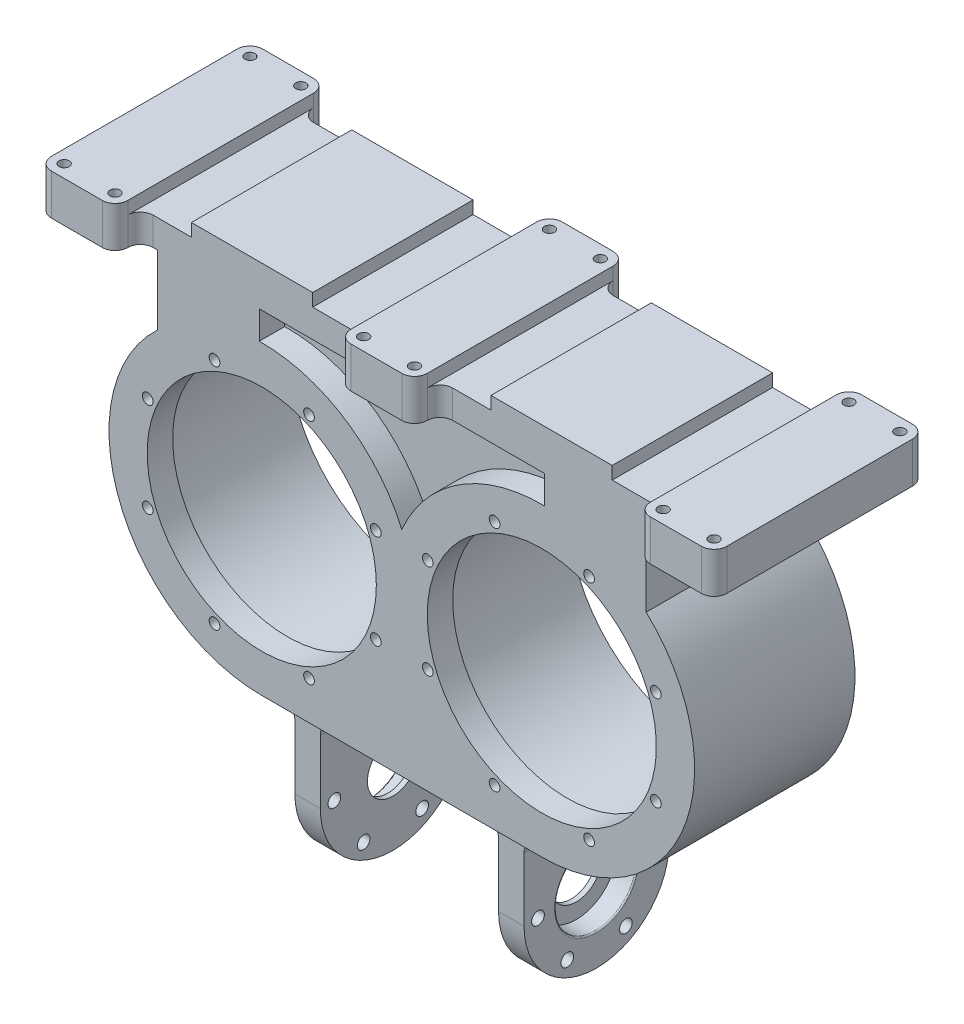
SolidWorks part; units mm, degrees
material "不锈钢 (铁素体)"
ref_plane "前视基准面" through (0, 0, 0) normal (0, 0, 1) x (1, 0, 0)
ref_plane "上视基准面" through (0, 0, 0) normal (0, 1, 0) x (1, 0, 0)
ref_plane "右视基准面" through (0, 0, 0) normal (1, 0, 0) x (0, 0, -1)
other "Configuration Table"
sketch "草图1" plane through (0, 0, 0) normal (0, 0, 1) x (1, 0, 0)
  line L0 (55, 3.4264) -> (55, 82.0697) construction
  line L1 (0, 0) -> (0, 52.5) construction
  line L2 (-40.9852, 43.8203) -> (-40.9852, 71.042)
  line L4 (110, 0) -> (110, 52.5) construction
  line L8 (150.9852, 43.8203) -> (150.9852, 71.042)
  line L10 (150.9852, 82.0697) -> (-40.9852, 82.0697)
  line L14 (0, -60) -> (110, -60)
  line L15 (-40.9852, 71.042) -> (-77.642, 71.042)
  line L16 (-77.642, 71.042) -> (-77.642, 82.0697)
  line L17 (-77.642, 82.0697) -> (-40.9852, 82.0697)
  line L18 (187.642, 82.0697) -> (150.9852, 82.0697)
  line L19 (150.9852, 71.042) -> (187.642, 71.042)
  line L20 (187.642, 71.042) -> (187.642, 82.0697)
  circle A0 centre (0, 0) radius 52.5
  arc A1 (-40.9852, 43.8203) -> (0, -60) centre (0, 0) ccw
  arc A2 (150.9852, 43.8203) -> (110, -60) centre (110, 0) cw
  circle A3 centre (110, 0) radius 52.5
  dimension "D1" = 105
  dimension "D2" = 60
  dimension "D3" = 110
extrude "凸台-拉伸1" add sketch "草图1" along normal blind 63
ref_plane "中心堆成面" through (55, 0, 0) normal (1, 0, 0) x (0, 0, -1)
ref_plane "基准面2" through (10, 0, 0) normal (1, 0, 0) x (0, 0, -1)
sketch "草图3" plane through (10, 0, 0) normal (1, 0, 0) x (0, 0, -1)
  line L6 (-60, -60) -> (-60, -90)
  line L7 (-63, -60) -> (0, -60) construction
  line L9 (-3, -90) -> (-3, -60)
  line L10 (-3, -60) -> (-60, -60)
  line L11 (-63, 43.8203) -> (-63, -60) construction
  line L12 (0, -60) -> (0, 43.8203) construction
  arc A4 (-60, -90) -> (-3, -90) centre (-31.5, -90) ccw
  circle A5 centre (-31.5, -90) radius 10
  dimension "D3" = 20
  dimension "D1" = 3
  dimension "D2" = 3
  dimension "D4" = 30
extrude "凸台-拉伸3" add sketch "草图3" along normal blind 10
sketch "草图5" plane through (0, 0, 3) normal (0, 0, -1) x (-1, 0, 0)
  line L1 (-15, -90) -> (-15, -82.99) construction
  line L5 (-20, -90) -> (-10, -90) construction
  line L6 (-20, -90) -> (-20, -60) construction
  line L7 (0, -60) -> (-110, -60) construction
  line L8 (-20, -65) -> (-20, -60)
  line L9 (-20, -60) -> (-25, -60)
  line L10 (-10, -65) -> (-10, -60)
  line L11 (-10, -60) -> (-5, -60)
  arc A1 (-20, -65) -> (-25, -60) centre (-25, -65) ccw
  arc A2 (-10, -65) -> (-5, -60) centre (-5, -65) cw
  dimension "D1" = 5
  dimension "D2" = 5
extrude "凸台-拉伸5" add sketch "草图5" against normal up to surface (57 mm away) up to face at (15, -75, 60)
mirror "镜向1" about plane through (55, 0, 0) normal (1, 0, 0) of "凸台-拉伸5", "凸台-拉伸3"
sketch "草图6" plane through (0, 0, 63) normal (0, 0, 1) x (1, 0, 0)
  line L0 (55, -34.65) -> (55, 34.65) construction
  circle A1 centre (0, 0) radius 45
  circle A3 centre (110, 0) radius 45
  circle A6 centre (0, 0) radius 52.5
  circle A7 centre (110, 0) radius 52.5
extrude "凸台-拉伸6" add sketch "草图6" against normal blind 10
sketch "草图9" plane through (0, 0, 63) normal (0, 0, 1) x (1, 0, 0)
  line L0 (61.5, 0) -> (110, 0) construction
  line L1 (110, 0) -> (89.2277, 8.6042) construction
  circle A0 centre (110, 0) radius 48.5 construction
  circle A1 centre (65.1918, 18.5601) radius 2.1
  circle A2 centre (91.4399, 44.8082) radius 2.1
  circle A3 centre (128.5601, 44.8082) radius 2.1
  circle A4 centre (154.8082, 18.5601) radius 2.1
  circle A5 centre (154.8082, -18.5601) radius 2.1
  circle A6 centre (128.5601, -44.8082) radius 2.1
  circle A7 centre (91.4399, -44.8082) radius 2.1
  circle A8 centre (65.1918, -18.5601) radius 2.1
  dimension "D1" = 8
  dimension "D2" = 22.5
  dimension "D3" = 48.5
extrude "切除-拉伸1" cut sketch "草图9" against normal blind 10
mirror "镜向2" about plane through (55, 0, 0) normal (1, 0, 0) of "切除-拉伸1"
sketch "草图10" plane through (0, 0, 63) normal (0, 0, 1) x (1, 0, 0)
  line L1 (110.9852, 59.9919) -> (110.9852, 71.042)
  line L2 (110.9852, 71.042) -> (-0.9852, 71.042)
  line L3 (-0.9852, 71.042) -> (-0.9852, 59.9919)
  line L4 (150.9852, 43.8203) -> (150.9852, 71.042) construction
  line L5 (-40.9852, 71.042) -> (-40.9852, 43.8203) construction
  line L7 (-77.642, 71.042) -> (-40.9852, 71.042) construction
  arc A2 (110.9852, 59.9919) -> (55, 23.9792) centre (110, 0) ccw
  arc A3 (55, 23.9792) -> (-0.9852, 59.9919) centre (0, 0) ccw
  dimension "D1" = 40
  dimension "D3" = 120
  dimension "D4" = 120
  dimension "D2" = 40
  dimension "D5" = 0
extrude "切除-拉伸2" cut sketch "草图10" against normal blind 10
sketch "草图11" plane through (10, 0, 0) normal (-1, 0, 0) x (0, 0, 1)
  circle A0 centre (31.5, -90) radius 16
  dimension "D1" = 32
extrude "切除-拉伸3" cut sketch "草图11" against normal blind 8
ref_plane "基准面3" through (0, 0, 31.5) normal (0, 0, 1) x (1, 0, 0)
mirror "镜向3" about plane through (0, 0, 31.5) normal (0, 0, 1) of "切除-拉伸2"
mirror "镜向4" about plane through (55, 0, 0) normal (1, 0, 0) of "切除-拉伸3"
fillet "圆角1" radius 0.5 2 edges at (100, -90, 47.5) (10, -90, 47.5)
sketch "草图13" plane through (0, 82.0697, 0) normal (0, 1, 0) x (1, 0, 0)
  line L0 (152.642, -63) -> (187.642, -63)
  line L1 (55, -63) -> (55, 0) construction
  line L4 (187.642, -63) -> (187.642, -68)
  line L5 (187.642, -63) -> (-77.642, -63) construction
  line L6 (162.642, -73) -> (182.642, -73)
  line L7 (187.642, 0) -> (-77.642, 0) construction
  line L8 (-52.642, -73) -> (-72.642, -73)
  line L9 (-77.642, -63) -> (-77.642, -68)
  line L10 (-42.642, -63) -> (-77.642, -63)
  line L11 (-77.642, -31.5) -> (187.642, -31.5) construction
  line L12 (-77.642, -63) -> (-77.642, 0) construction
  line L13 (187.642, -63) -> (187.642, 0) construction
  line L14 (162.642, 10) -> (182.642, 10)
  line L15 (187.642, 0) -> (187.642, 5)
  line L16 (152.642, 0) -> (187.642, 0)
  line L17 (-42.642, 0) -> (-77.642, 0)
  line L18 (-77.642, 0) -> (-77.642, 5)
  line L19 (-52.642, 10) -> (-72.642, 10)
  line L20 (45, -73) -> (65, -73)
  line L22 (75, -63) -> (35, -63)
  line L23 (75, 0) -> (35, 0)
  line L24 (45, 10) -> (65, 10)
  arc A2 (182.642, -73) -> (187.642, -68) centre (182.642, -68) ccw
  arc A3 (157.642, -68) -> (162.642, -73) centre (162.642, -68) ccw
  arc A4 (157.642, -68) -> (152.642, -63) centre (152.642, -68) ccw
  arc A5 (-47.642, -68) -> (-52.642, -73) centre (-52.642, -68) cw
  arc A6 (-72.642, -73) -> (-77.642, -68) centre (-72.642, -68) cw
  arc A7 (-47.642, -68) -> (-42.642, -63) centre (-42.642, -68) cw
  arc A8 (157.642, 5) -> (162.642, 10) centre (162.642, 5) cw
  arc A9 (182.642, 10) -> (187.642, 5) centre (182.642, 5) cw
  arc A10 (157.642, 5) -> (152.642, 0) centre (152.642, 5) cw
  arc A11 (-47.642, 5) -> (-42.642, 0) centre (-42.642, 5) ccw
  arc A12 (-72.642, 10) -> (-77.642, 5) centre (-72.642, 5) ccw
  arc A13 (-47.642, 5) -> (-52.642, 10) centre (-52.642, 5) ccw
  arc A16 (40, -68) -> (35, -63) centre (35, -68) ccw
  arc A18 (40, -68) -> (45, -73) centre (45, -68) ccw
  arc A19 (70, -68) -> (65, -73) centre (65, -68) cw
  arc A20 (70, -68) -> (75, -63) centre (75, -68) cw
  arc A21 (70, 5) -> (75, 0) centre (75, 5) ccw
  arc A22 (40, 5) -> (35, 0) centre (35, 5) cw
  arc A23 (40, 5) -> (45, 10) centre (45, 5) cw
  arc A24 (70, 5) -> (65, 10) centre (65, 5) ccw
  dimension "D2" = 5
  dimension "D4" = 5
  dimension "D5" = 10
  dimension "D6" = 10
  dimension "D7" = 20
  dimension "D1" = 5
  dimension "D3" = 20
  dimension "D8" = 10
extrude "凸台-拉伸7" add sketch "草图13" against normal up to surface (11.0278 mm away) up to face at (169.3136, 71.042, 31.5)
sketch "草图14" plane through (10, 0, 0) normal (-1, 0, 0) x (0, 0, 1)
  circle A0 centre (31.5, -90) radius 23 construction
  circle A1 centre (8.5, -90) radius 2.5
  circle A2 centre (20, -70.0814) radius 2.5
  circle A3 centre (43, -70.0814) radius 2.5
  circle A4 centre (54.5, -90) radius 2.5
  circle A5 centre (43, -109.9186) radius 2.5
  circle A6 centre (20, -109.9186) radius 2.5
  dimension "D1" = 5
  dimension "D2" = 6
extrude "切除-拉伸5" cut sketch "草图14" against normal blind 135
sketch "草图15" plane through (0, 82.0697, 0) normal (0, 1, 0) x (1, 0, 0)
  line L0 (-110.3133, -31.5) -> (110.3133, -31.5) construction
  circle A0 centre (-72.642, 5) radius 2
  circle A1 centre (-52.642, 5) radius 2
  circle A2 centre (45, 5) radius 2
  circle A3 centre (65, 5) radius 2
  circle A4 centre (162.642, 5) radius 2
  circle A5 centre (182.642, 5) radius 2
  circle A6 centre (-72.642, -68) radius 2
  circle A7 centre (-52.642, -68) radius 2
  circle A8 centre (45, -68) radius 2
  circle A9 centre (65, -68) radius 2
  circle A10 centre (162.642, -68) radius 2
  circle A11 centre (182.642, -68) radius 2
sketch "草图16" plane through (0, 82.0697, 0) normal (0, 1, 0) x (1, 0, 0)
  line L0 (-72.642, -73) -> (-52.642, -73)
  line L1 (-47.642, -68) -> (-47.642, 5)
  line L2 (-52.642, 10) -> (-72.642, 10)
  line L3 (-77.642, 5) -> (-77.642, -68)
  line L4 (40, -68) -> (40, 5)
  line L5 (45, 10) -> (65, 10)
  line L6 (70, 5) -> (70, -68)
  line L7 (65, -73) -> (45, -73)
  line L8 (55, -45.65) -> (55, 45.65) construction
  line L9 (162.642, 10) -> (182.642, 10)
  line L10 (157.642, -68) -> (157.642, 5)
  line L11 (182.642, -73) -> (162.642, -73)
  line L12 (187.642, 5) -> (187.642, -68)
  line L13 (152.642, 0) -> (75, 0) construction
  line L14 (90, 0) -> (137.642, 0)
  line L15 (90, 0) -> (90, -63)
  line L16 (90, -63) -> (137.642, -63)
  line L17 (137.642, 0) -> (137.642, -63)
  line L18 (152.642, -63) -> (75, -63) construction
  line L24 (20, -63) -> (-27.642, -63)
  line L25 (-27.642, 0) -> (-27.642, -63)
  line L26 (20, 0) -> (-27.642, 0)
  line L27 (20, 0) -> (20, -63)
  arc A0 (-72.642, 10) -> (-77.642, 5) centre (-72.642, 5) ccw
  arc A1 (-47.642, 5) -> (-52.642, 10) centre (-52.642, 5) ccw
  arc A2 (-52.642, -73) -> (-47.642, -68) centre (-52.642, -68) ccw
  arc A3 (-77.642, -68) -> (-72.642, -73) centre (-72.642, -68) ccw
  arc A4 (45, 10) -> (40, 5) centre (45, 5) ccw
  arc A5 (70, 5) -> (65, 10) centre (65, 5) ccw
  arc A6 (65, -73) -> (70, -68) centre (65, -68) ccw
  arc A7 (40, -68) -> (45, -73) centre (45, -68) ccw
  arc A8 (157.642, 5) -> (162.642, 10) centre (162.642, 5) cw
  arc A9 (162.642, -73) -> (157.642, -68) centre (162.642, -68) cw
  arc A10 (187.642, -68) -> (182.642, -73) centre (182.642, -68) cw
  arc A11 (182.642, 10) -> (187.642, 5) centre (182.642, 5) cw
  dimension "D1" = 20
  dimension "D2" = 20
extrude "凸台-拉伸8" add sketch "草图16" along normal blind 5
extrude "切除-拉伸7" cut sketch "草图15" against normal mid plane 28
